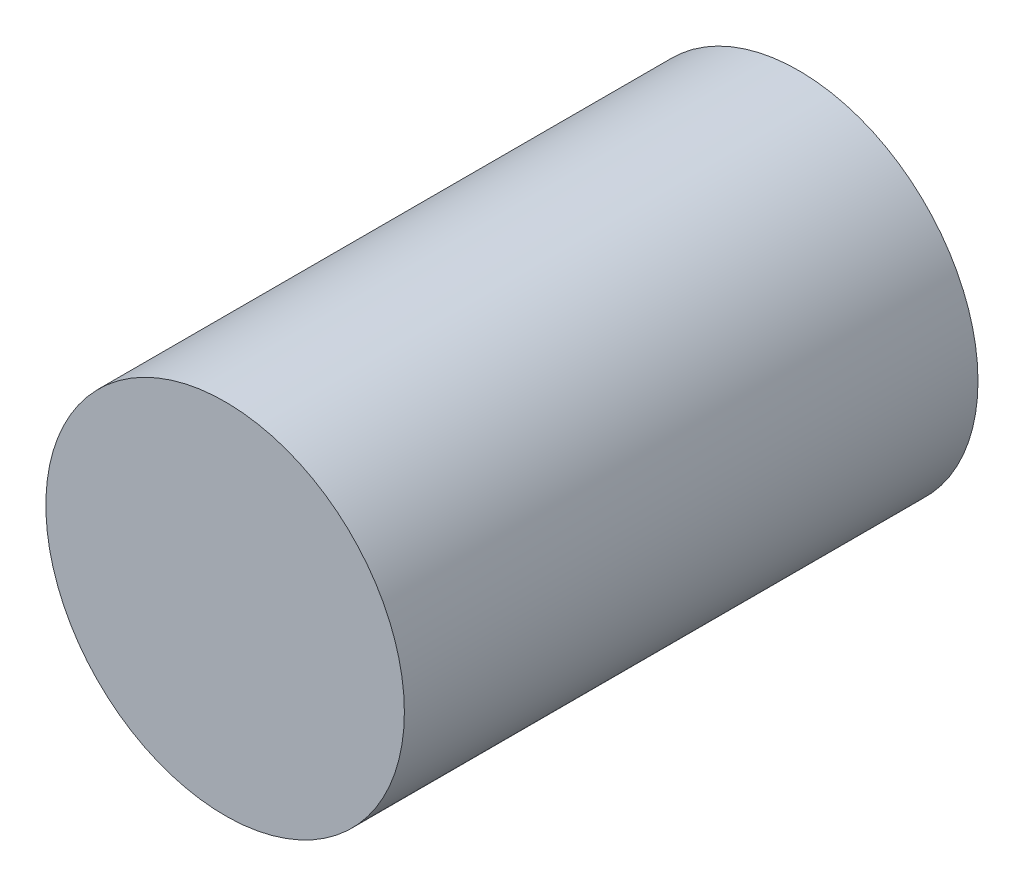
SolidWorks part; units mm, degrees
material "ABS"
ref_plane "Front Plane" through (0, 0, 0) normal (0, 0, 1) x (1, 0, 0)
ref_plane "Top Plane" through (0, 0, 0) normal (0, 1, 0) x (1, 0, 0)
ref_plane "Right Plane" through (0, 0, 0) normal (1, 0, 0) x (0, 0, -1)
sketch "Sketch1" plane through (0, 0, 0) normal (0, 0, 1) x (1, 0, 0)
  circle A0 centre (0, 0) radius 1.5875
extrude "Boss-Extrude1" add sketch "Sketch1" along normal blind 5.08
